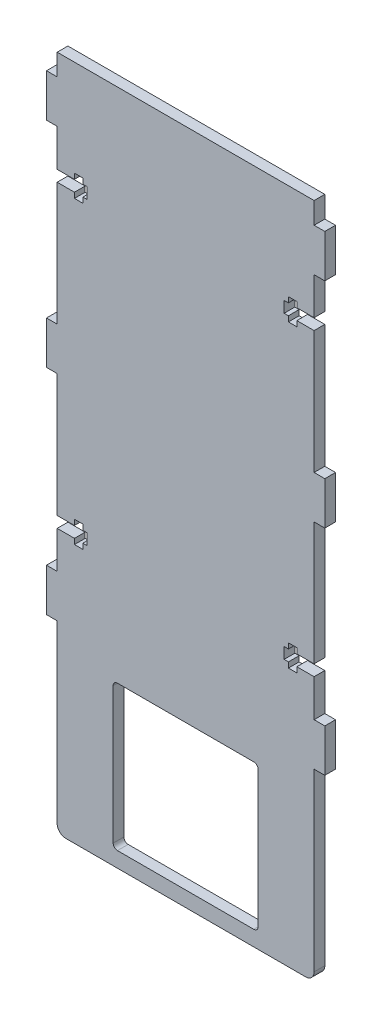
SolidWorks part; units mm, degrees
ref_plane "Front Plane" through (0, 0, 0) normal (0, 0, 1) x (1, 0, 0)
ref_plane "Top Plane" through (0, 0, 0) normal (0, 1, 0) x (1, 0, 0)
ref_plane "Right Plane" through (0, 0, 0) normal (1, 0, 0) x (0, 0, -1)
sketch "Sketch1" plane through (0, 0, 0) normal (0, 0, 1) x (1, 0, 0)
  line L1 (0, 0) -> (76.2, 0)
  line L2 (0, 0) -> (0, 152.4)
  line L3 (0, 152.4) -> (76.2, 152.4)
  line L4 (76.2, 0) -> (76.2, 152.4)
  dimension "D1" = 152.4
  dimension "D2" = 76.2
extrude "Boss-Extrude1" add sketch "Sketch1" along normal blind 3.175
sketch "Sketch2" plane through (0, 0, 3.175) normal (0, 0, 1) x (1, 0, 0)
  line L0 (0, 76.2) -> (76.2, 76.2) construction
  line L1 (0, 146.05) -> (-3.175, 146.05)
  line L2 (0, 146.05) -> (0, 133.35)
  line L3 (0, 133.35) -> (-3.175, 133.35)
  line L4 (-3.175, 146.05) -> (-3.175, 133.35)
  line L5 (0, 6.35) -> (-3.175, 6.35)
  line L6 (0, 6.35) -> (0, 19.05)
  line L7 (0, 19.05) -> (-3.175, 19.05)
  line L8 (-3.175, 6.35) -> (-3.175, 19.05)
  line L9 (0, 152.4) -> (0, 0) construction
  line L10 (76.2, 0) -> (76.2, 152.4) construction
  line L11 (-3.175, 76.2) -> (0, 76.2) construction
  line L12 (0, 82.55) -> (-3.175, 82.55)
  line L13 (0, 82.55) -> (0, 69.85)
  line L14 (0, 69.85) -> (-3.175, 69.85)
  line L15 (-3.175, 82.55) -> (-3.175, 69.85)
  line L16 (38.1, 152.4) -> (38.1, 0) construction
  line L17 (76.2, 152.4) -> (0, 152.4) construction
  line L18 (0, 0) -> (76.2, 0) construction
  line L19 (79.375, 146.05) -> (79.375, 133.35)
  line L20 (76.2, 133.35) -> (79.375, 133.35)
  line L21 (76.2, 146.05) -> (76.2, 133.35)
  line L22 (76.2, 146.05) -> (79.375, 146.05)
  line L23 (0, 82.55) -> (-3.175, 82.55)
  line L24 (0, 69.85) -> (-3.175, 69.85)
  line L25 (0, 82.55) -> (-3.175, 82.55)
  line L26 (0, 69.85) -> (-3.175, 69.85)
  line L27 (0, 82.55) -> (-3.175, 82.55)
  line L28 (0, 69.85) -> (-3.175, 69.85)
  line L29 (79.375, 6.35) -> (79.375, 19.05)
  line L30 (76.2, 19.05) -> (79.375, 19.05)
  line L31 (76.2, 6.35) -> (76.2, 19.05)
  line L32 (76.2, 6.35) -> (79.375, 6.35)
  line L33 (0, 82.55) -> (-3.175, 82.55)
  line L34 (0, 69.85) -> (-3.175, 69.85)
  line L35 (0, 82.55) -> (-3.175, 82.55)
  line L36 (0, 69.85) -> (-3.175, 69.85)
  line L37 (0, 82.55) -> (-3.175, 82.55)
  line L38 (0, 69.85) -> (-3.175, 69.85)
  line L39 (0, 82.55) -> (-3.175, 82.55)
  line L40 (0, 69.85) -> (-3.175, 69.85)
  line L41 (79.375, 76.2) -> (76.2, 76.2) construction
  line L42 (76.2, 69.85) -> (79.375, 69.85)
  line L43 (76.2, 82.55) -> (79.375, 82.55)
  line L44 (76.2, 69.85) -> (79.375, 69.85)
  line L45 (76.2, 82.55) -> (79.375, 82.55)
  line L46 (76.2, 69.85) -> (79.375, 69.85)
  line L47 (76.2, 82.55) -> (79.375, 82.55)
  line L48 (76.2, 69.85) -> (79.375, 69.85)
  line L49 (76.2, 82.55) -> (79.375, 82.55)
  line L50 (76.2, 69.85) -> (79.375, 69.85)
  line L51 (76.2, 82.55) -> (79.375, 82.55)
  line L52 (76.2, 69.85) -> (79.375, 69.85)
  line L53 (76.2, 82.55) -> (79.375, 82.55)
  line L54 (76.2, 69.85) -> (79.375, 69.85)
  line L55 (76.2, 82.55) -> (79.375, 82.55)
  line L56 (79.375, 82.55) -> (79.375, 69.85)
  line L57 (76.2, 69.85) -> (79.375, 69.85)
  line L58 (76.2, 82.55) -> (76.2, 69.85)
  line L59 (76.2, 82.55) -> (79.375, 82.55)
  line M1 (0, 152.4) -> (0, 0)
  line M3 (76.2, 0) -> (76.2, 152.4)
  dimension "D1" = 3.175
  dimension "D2" = 12.7
  dimension "D3" = 12.7
  dimension "D4" = 12.7
  dimension "D5" = 3.175
  dimension "D6" = 6.35
  dimension "D7" = 6.35
extrude "Boss-Extrude3" add sketch "Sketch2" against normal blind 3.175 contours L12 L15 L14 M1 | L22 L20 L19 M3 | L56 L43 L42 M3 | L32 L29 L30 M3 | L8 L5 L7 M1 | L4 L3 L2 L1
sketch "Sketch4" plane through (0, 0, 3.175) normal (0, 0, 1) x (1, 0, 0)
  line L0 (38.1, 152.4) -> (38.1, 0) construction
  line L1 (76.2, 152.4) -> (0, 152.4) construction
  line L2 (0, 0) -> (76.2, 0) construction
  line L3 (0, 133.35) -> (0, 82.55) construction
  line L4 (0, 122.301) -> (8.89, 122.301)
  line L5 (0, 122.301) -> (0, 118.999)
  line L6 (0, 118.999) -> (8.89, 118.999)
  line L7 (8.89, 122.301) -> (8.89, 118.999)
  line L8 (5.12, 120.65) -> (7.62, 120.65) construction
  line L9 (5.12, 123.9) -> (7.62, 123.9)
  line L10 (5.12, 123.9) -> (5.12, 117.4)
  line L11 (5.12, 117.4) -> (7.62, 117.4)
  line L12 (7.62, 123.9) -> (7.62, 117.4)
  line L13 (0, 120.65) -> (8.89, 120.65) construction
  line L14 (0, 133.35) -> (-3.175, 133.35) construction
  line L15 (-3.175, 76.2) -> (79.375, 76.2) construction
  line L16 (-3.175, 82.55) -> (-3.175, 69.85) construction
  line L17 (79.375, 82.55) -> (79.375, 69.85) construction
  line L18 (0, 31.75) -> (8.89, 31.75) construction
  line L19 (5.12, 31.75) -> (7.62, 31.75) construction
  line L20 (7.62, 28.5) -> (7.62, 35)
  line L21 (5.12, 35) -> (7.62, 35)
  line L22 (5.12, 28.5) -> (5.12, 35)
  line L23 (5.12, 28.5) -> (7.62, 28.5)
  line L24 (8.89, 30.099) -> (8.89, 33.401)
  line L25 (0, 33.401) -> (8.89, 33.401)
  line L26 (0, 30.099) -> (0, 33.401)
  line L27 (0, 30.099) -> (8.89, 30.099)
  line L28 (71.08, 31.75) -> (68.58, 31.75) construction
  line L29 (76.2, 31.75) -> (67.31, 31.75) construction
  line L30 (76.2, 120.65) -> (67.31, 120.65) construction
  line L31 (71.08, 120.65) -> (68.58, 120.65) construction
  line L32 (76.2, 30.099) -> (67.31, 30.099)
  line L33 (76.2, 30.099) -> (76.2, 33.401)
  line L34 (76.2, 33.401) -> (67.31, 33.401)
  line L35 (67.31, 30.099) -> (67.31, 33.401)
  line L36 (71.08, 28.5) -> (68.58, 28.5)
  line L37 (71.08, 28.5) -> (71.08, 35)
  line L38 (71.08, 35) -> (68.58, 35)
  line L39 (68.58, 28.5) -> (68.58, 35)
  line L40 (68.58, 123.9) -> (68.58, 117.4)
  line L41 (71.08, 117.4) -> (68.58, 117.4)
  line L42 (71.08, 123.9) -> (71.08, 117.4)
  line L43 (71.08, 123.9) -> (68.58, 123.9)
  line L44 (67.31, 122.301) -> (67.31, 118.999)
  line L45 (76.2, 118.999) -> (67.31, 118.999)
  line L46 (76.2, 122.301) -> (76.2, 118.999)
  line L47 (76.2, 122.301) -> (67.31, 122.301)
  dimension "D1" = 3.302
  dimension "D2" = 6.5
  dimension "D3" = 2.5
  dimension "D4" = 1.27
  dimension "D5" = 8.89
  dimension "D6" = 12.7
extrude "Cut-Extrude4" cut sketch "Sketch4" against normal blind 3.175 contours L6 L7 L4 L5 | L9 L12 L11 L10 | L21 L20 L23 L22 | L24 L25 L26 L27 | L35 L34 L33 L32 | L38 L39 L36 L37 | L41 L40 L43 L42 | L45 L44 L47 L46
sketch "Sketch5" plane through (0, 0, 3.175) normal (0, 0, 1) x (1, 0, 0)
  line L0 (0, 0) -> (76.2, 0) construction
  line L1 (0, 0) -> (76.2, 0)
  line L2 (0, 0) -> (0, -44.45)
  line L3 (0, -44.45) -> (76.2, -44.45)
  line L4 (76.2, 0) -> (76.2, -44.45)
  line L5 (38.1, 0) -> (38.1, -44.45) construction
  line L6 (0, -22.225) -> (76.2, -22.225) construction
  line L8 (16.6, -0.725) -> (59.6, -0.725)
  line L9 (16.6, -0.725) -> (16.6, -43.725)
  line L10 (16.6, -43.725) -> (59.6, -43.725)
  line L11 (59.6, -0.725) -> (59.6, -43.725)
  line L12 (16.6, -0.725) -> (59.6, -43.725) construction
  line L13 (16.6, -43.725) -> (59.6, -0.725) construction
  point P12 (38.1, -22.225)
  dimension "D1" = 44.45
  dimension "D2" = 43
  dimension "D3" = 43
extrude "Boss-Extrude4" add sketch "Sketch5" against normal blind 3.175
sketch "Sketch7" plane through (0, 0, 3.175) normal (0, 0, 1) x (1, 0, 0)
  line L0 (76.2, -44.45) -> (76.2, 6.35) construction
  line L1 (0, -44.45) -> (76.2, -44.45)
  line L2 (0, -44.45) -> (0, -48.26)
  line L3 (0, -48.26) -> (76.2, -48.26)
  line L4 (76.2, -44.45) -> (76.2, -48.26)
  dimension "D1" = 3.81
extrude "Boss-Extrude5" add sketch "Sketch7" against normal blind 3.175
fillet "Fillet1" radius 2.54 2 edges at (76.2, -48.26, 1.5875) (0, -48.26, 1.5875)
fillet "Fillet2" radius 1.27 4 edges at (59.6, -43.725, 1.5875) (59.6, -0.725, 1.5875) (16.6, -0.725, 1.5875) (16.6, -43.725, 1.5875)
